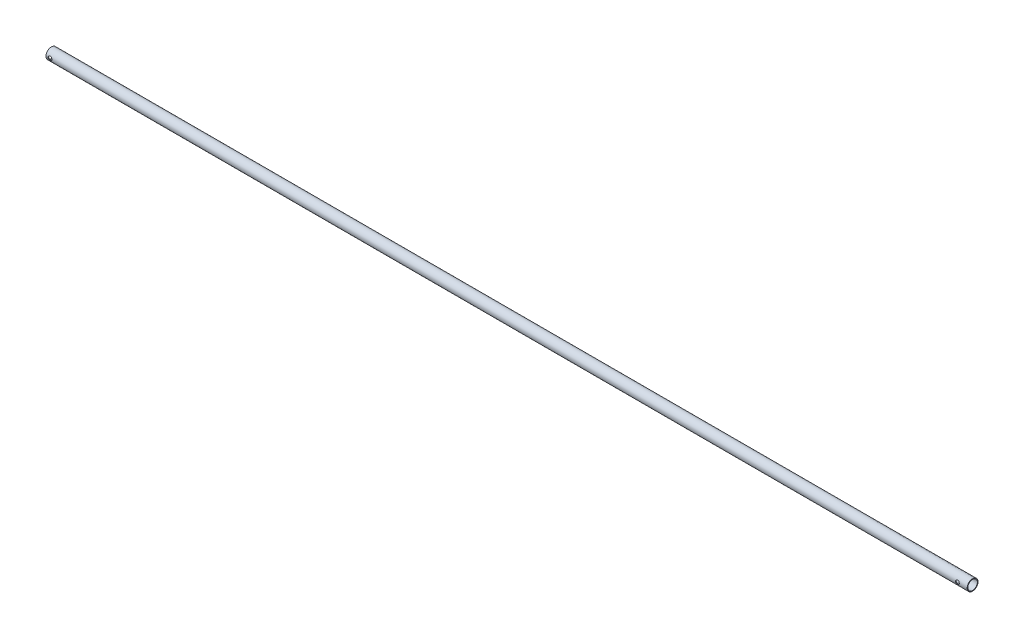
SolidWorks part; units mm, degrees
material "Galvanized Steel"
ref_plane "Front Plane" through (0, 0, 0) normal (0, 0, 1) x (1, 0, 0)
ref_plane "Top Plane" through (0, 0, 0) normal (0, 1, 0) x (1, 0, 0)
ref_plane "Right Plane" through (0, 0, 0) normal (1, 0, 0) x (0, 0, -1)
sketch "Sketch1" plane through (0, 0, 0) normal (1, 0, 0) x (0, 0, -1)
  circle A0 centre (0, 0) radius 7.8994
  circle A1 centre (0, 0) radius 8.9662
  dimension "D1" = 15.7988
  dimension "D2" = 17.9324
extrude "Boss-Extrude1" add sketch "Sketch1" along normal blind 1524
sketch "Sketch2" plane through (0, 0, 0) normal (0, 0, 1) x (1, 0, 0)
  circle A0 centre (1507.7967, 0) radius 3.175
  circle A1 centre (6.5108, 0) radius 3.175
extrude "Cut-Extrude1" cut sketch "Sketch2" against normal through all and the other way through all
